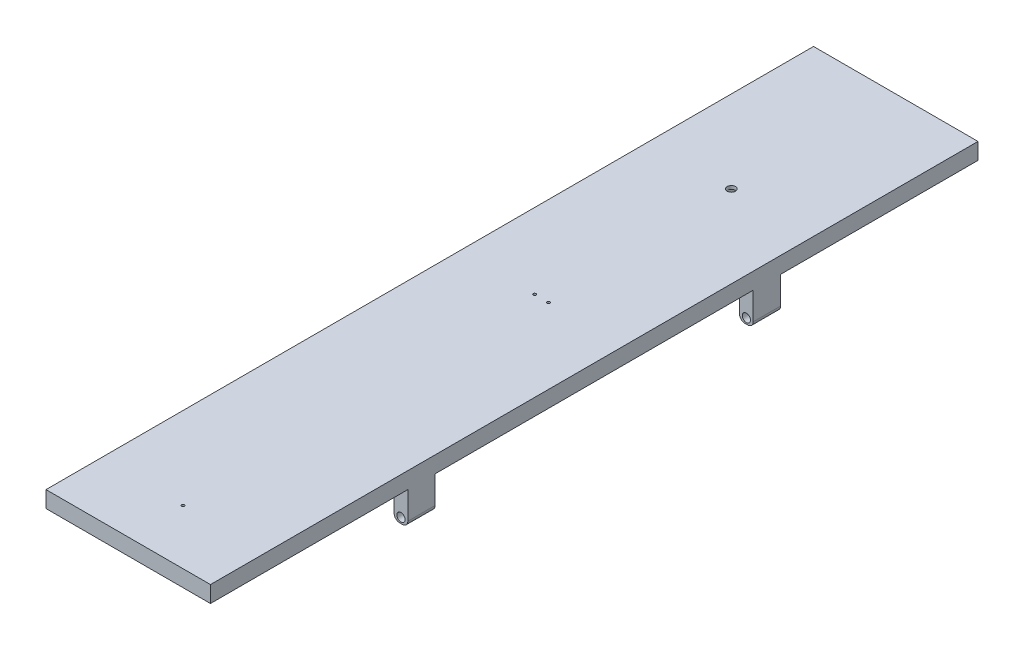
SolidWorks part; units mm, degrees
ref_plane "Front Plane" through (0, 0, 0) normal (0, 0, 1) x (1, 0, 0)
ref_plane "Top Plane" through (0, 0, 0) normal (0, 1, 0) x (1, 0, 0)
ref_plane "Right Plane" through (0, 0, 0) normal (1, 0, 0) x (0, 0, -1)
sketch "Sketch1" plane through (0, 0, 0) normal (0, 0, 1) x (1, 0, 0)
  line L0 (0, 0) -> (0, 30)
  line L1 (0, 30) -> (-300, 30)
  line L2 (-25, 0) -> (-275, 0)
  line L3 (-300, 0) -> (-300, 30)
  line L4 (0, 0) -> (0, -50)
  line L5 (-10, -60) -> (-15, -60)
  line L6 (-25, -50) -> (-25, 0)
  line L8 (-150, 30) -> (-150, -148.6923) construction
  line L9 (-290, -60) -> (-285, -60)
  line L10 (-300, 0) -> (-300, -50)
  line L11 (-275, -50) -> (-275, 0)
  circle A0 centre (-12.5, -50) radius 7.5
  arc A1 (0, -50) -> (-10, -60) centre (-10, -50) cw
  arc A2 (-15, -60) -> (-25, -50) centre (-15, -50) cw
  arc A3 (-285, -60) -> (-275, -50) centre (-285, -50) ccw
  arc A4 (-300, -50) -> (-290, -60) centre (-290, -50) ccw
  circle A5 centre (-287.5, -50) radius 7.5
  point P14 (-25, -60)
  dimension "D3" = 15
  dimension "D4" = 12.5
  dimension "D5" = 50
  dimension "D8" = 10
  dimension "D9" = 30
  dimension "D1" = 300
  dimension "D2" = 30
  dimension "D6" = 60
  dimension "D7" = 25
extrude "Boss-Extrude1" add sketch "Sketch1" along normal blind 1100 and the other way blind 300
sketch "Sketch3" plane through (0, 0, 0) normal (1, 0, 0) x (0, 0, -1)
  line L0 (-1100, 0) -> (-740, 0)
  line L1 (-1100, -50) -> (-1100, 30) construction
  line L2 (-740, 0) -> (-740, -60)
  line L3 (-1100, -60) -> (300, -60) construction
  line L4 (-740, -60) -> (-1100, -60)
  line L5 (-1100, -60) -> (-1100, 0)
  line L6 (0, 0) -> (300, 0)
  line L7 (0, 0) -> (-1100, 0) construction
  line L10 (-60, 0) -> (-60, -60)
  line L11 (-60, -60) -> (0, -60)
  line L12 (0, 0) -> (-60, 0)
  line L14 (-690, -60) -> (-110, -60)
  line L17 (-690, -60) -> (-690, -50)
  line L18 (-1100, -50) -> (300, -50) construction
  line L20 (-110, -50) -> (-110, -60)
  line L21 (300, 0) -> (300, -60)
  line L22 (300, -60) -> (0, -60)
  line L23 (-110, -50) -> (-110, 0)
  line L24 (-110, 0) -> (-690, 0)
  line L25 (-690, 0) -> (-690, -50)
  line L27 (300, -50) -> (300, 30) construction
  point P14 (-550, 0)
  dimension "D1" = 580
  dimension "D2" = 410
  dimension "D3" = 50
  dimension "D4" = 50
  dimension "D5" = 60
  dimension "D6" = 60
extrude "Cut-Extrude1" cut sketch "Sketch3" against normal through all and the other way through all
sketch "Sketch4" plane through (0, 30, 0) normal (0, 1, 0) x (1, 0, 0)
  line L0 (0, 300) -> (-300, 300) construction
  line L1 (-150, 300) -> (-150, -1100) construction
  line L2 (0, -1100) -> (-300, -1100) construction
  circle A0 centre (-150, 0) radius 7.5
  dimension "D1" = 15
  dimension "D2" = 1100
extrude "Cut-Extrude2" cut sketch "Sketch4" against normal through all
sketch "Sketch7" plane through (0, 0, 0) normal (0, -1, 0) x (-1, 0, 0)
  line L1 (162.5, -16) -> (137.5, -16)
  line L2 (162.5, -16) -> (162.5, 16)
  line L3 (162.5, 16) -> (137.5, 16)
  line L4 (137.5, -16) -> (137.5, 16)
  line L5 (162.5, -16) -> (137.5, 16) construction
  line L6 (162.5, 16) -> (137.5, -16) construction
  point P0 (150, 0)
  dimension "D1" = 25
  dimension "D2" = 32
extrude "Boss-Extrude2" add sketch "Sketch7" along normal blind 37.5
sketch "Sketch8" plane through (0, 0, 16) normal (0, 0, 1) x (1, 0, 0)
  line L5 (-137.5, 0) -> (-162.5, 0) construction
  line L6 (-158, 0) -> (-142, 0)
  line L7 (-158, 0) -> (-158, -32.5)
  line L8 (-158, -32.5) -> (-142, -32.5)
  line L9 (-142, 0) -> (-142, -32.5)
  line L10 (-162.5, -37.5) -> (-162.5, 0) construction
  dimension "D1" = 16
  dimension "D2" = 4.5
  dimension "D3" = 32.5
extrude "Cut-Extrude4" cut sketch "Sketch8" against normal through all
sketch "Sketch9" plane through (0, 0, 0) normal (0, -1, 0) x (1, 0, 0)
  line L1 (-158, 32) -> (-142, 32)
  line L2 (-158, 32) -> (-158, -32)
  line L3 (-158, -32) -> (-142, -32)
  line L4 (-142, 32) -> (-142, -32)
  line L5 (-158, 32) -> (-142, -32) construction
  line L6 (-158, -32) -> (-142, 32) construction
  point P0 (-150, 0)
  dimension "D1" = 16
  dimension "D2" = 64
extrude "Cut-Extrude5" cut sketch "Sketch9" against normal blind 24
sketch "Sketch10" plane through (0, 30, 0) normal (0, 1, 0) x (1, 0, 0)
  line L0 (-150, -1100) -> (-150, 300) construction
  line L1 (0, -1100) -> (-300, -1100) construction
  line L2 (0, 300) -> (-300, 300) construction
  line L3 (-162.7, -345.95) -> (-137.3, -345.95) construction
  line L4 (-300, -300) -> (0, -300) construction
  line L5 (-300, 300) -> (-300, -1100) construction
  line L6 (0, 300) -> (0, -1100) construction
  circle A0 centre (-150, -1000) radius 2.5908
  circle A1 centre (-162.7, -345.95) radius 2.5908
  circle A3 centre (-137.3, -345.95) radius 2.5908
  dimension "D1" = 5.1816
  dimension "D2" = 5.1816
  dimension "D3" = 12.7
  dimension "D4" = 5.1816
  dimension "D5" = 25.4
  dimension "D6" = 700
  dimension "D7" = 654.05
  dimension "D8" = 600
extrude "Cut-Extrude6" cut sketch "Sketch10" against normal blind 20
